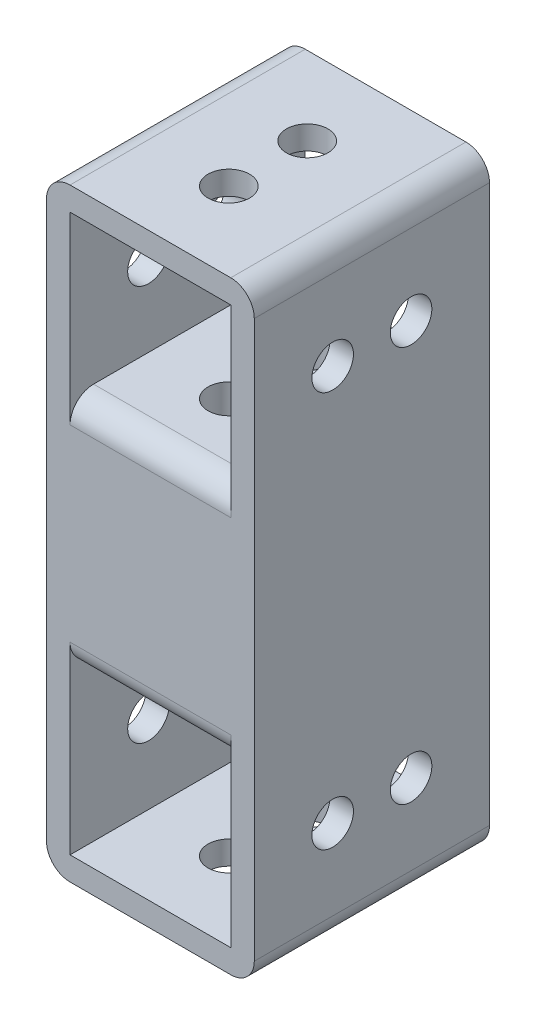
SolidWorks part; units mm, degrees
ref_plane "前视基准面" through (0, 0, 0) normal (0, 0, 1) x (1, 0, 0)
ref_plane "上视基准面" through (0, 0, 0) normal (0, 1, 0) x (1, 0, 0)
ref_plane "右视基准面" through (0, 0, 0) normal (1, 0, 0) x (0, 0, -1)
other "Configuration Table"
sketch "草图1" plane through (0, 0, 0) normal (0, 0, 1) x (1, 0, 0)
  line L0 (-10.25, 10.25) -> (-10.25, 40.25)
  line L1 (-10.25, -10.25) -> (10.25, -10.25)
  line L2 (-10.25, -10.25) -> (-10.25, 10.25)
  line L3 (-10.25, 10.25) -> (10.25, 10.25)
  line L4 (10.25, -10.25) -> (10.25, 10.25)
  line L5 (-10.25, -10.25) -> (10.25, 10.25) construction
  line L6 (-10.25, 10.25) -> (10.25, -10.25) construction
  line L7 (10.25, 40.25) -> (10.25, 10.25)
  line L8 (-10.25, 40.25) -> (10.25, 40.25)
  line L9 (-10.25, 40.25) -> (-10.25, 60.75)
  line L10 (-10.25, 60.75) -> (10.25, 60.75)
  line L11 (10.25, 40.25) -> (10.25, 60.75)
  line L12 (-13.25, 40.25) -> (-13.25, 63.75)
  line L13 (-13.25, 63.75) -> (13.25, 63.75)
  line L14 (13.25, 40.25) -> (13.25, 63.75)
  line L15 (-13.25, 10.25) -> (-13.25, 40.25)
  line L16 (13.25, 40.25) -> (13.25, 10.25)
  line L17 (13.25, -13.25) -> (13.25, 10.25)
  line L18 (-13.25, -13.25) -> (13.25, -13.25)
  line L19 (-13.25, -13.25) -> (-13.25, 10.25)
  point P0 (0, 0)
  dimension "D1" = 20.5
  dimension "D2" = 20.5
  dimension "D3" = 30
  dimension "D4" = 20.5
  dimension "D5" = 20.5
  dimension "D6" = 3
extrude "凸台-拉伸1" add sketch "草图1" along normal blind 30 contours L19 L18 L17 L16 L14 L13 L12 L15 L11 L7 L4 L1 L2 L0 L9 L10 | L8 L0 L3 L7
fillet "圆角1" radius 3 4 edges at (-13.25, 63.75, 15) (13.25, 63.75, 15) (13.25, -13.25, 15) (-13.25, -13.25, 15)
sketch "草图2" plane through (0, 63.75, 0) normal (0, 1, 0) x (1, 0, 0)
  line L0 (0, 0) -> (0, -10)
  line L1 (-10.25, 0) -> (10.25, 0) construction
  line L2 (0, -10) -> (0, -20)
  circle A0 centre (0, -10) radius 2.65
  circle A1 centre (0, -20) radius 2.65
  dimension "D2" = 5.3
  dimension "D4" = 5.3
  dimension "D1" = 10
  dimension "D3" = 10
extrude "切除-拉伸1" cut sketch "草图2" against normal through all contours A0 | A1
sketch "草图3" plane through (13.25, 0, 0) normal (1, 0, 0) x (0, 0, -1)
  line L0 (-1030, 25.25) -> (48970, 25.25) construction
  line L1 (-30, -10.25) -> (-30, 60.75) construction
  line L2 (0, 0) -> (-10, 0)
  line L3 (-10, 0) -> (-20, 0)
  circle A0 centre (-10, 0) radius 2.65
  circle A1 centre (-20, 0) radius 2.65
  circle A2 centre (-10, 50.5) radius 2.65
  circle A3 centre (-20, 50.5) radius 2.65
  point P5 (-30, 25.25)
  dimension "D2" = 5.3
  dimension "D4" = 5.3
  dimension "D1" = 10
  dimension "D3" = 10
extrude "切除-拉伸2" cut sketch "草图3" against normal through all
fillet "圆角2" radius 3 4 edges at (0, 40.25, 0) (0, 10.25, 0) (0, 40.25, 30) (0, 10.25, 30)
